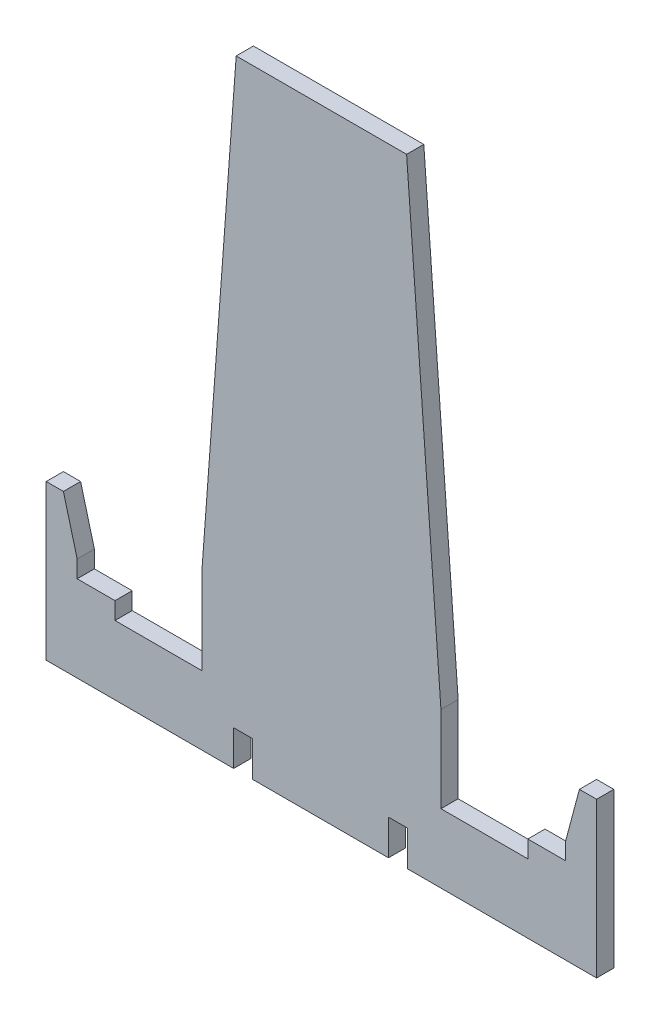
SolidWorks part; units mm, degrees
material "Plain Carbon Steel"
ref_plane "Front Plane" through (0, 0, 0) normal (0, 0, 1) x (1, 0, 0)
ref_plane "Top Plane" through (0, 0, 0) normal (0, 1, 0) x (1, 0, 0)
ref_plane "Right Plane" through (0, 0, 0) normal (1, 0, 0) x (0, 0, -1)
sketch "Model" plane through (0, 0, 0) normal (0, 0, 1) x (1, 0, 0)
  line L0 (-681.253, -108.7291) -> (-686.253, -108.7291)
  line L1 (-535.253, -123.7291) -> (-531.253, -108.7291)
  line L2 (-686.253, -153.7291) -> (-631.753, -153.7291)
  line L3 (-526.253, -153.7291) -> (-581.253, -153.7291)
  line L4 (-571.503, -133.7291) -> (-546.253, -133.7291)
  line L5 (-581.253, -153.7291) -> (-581.253, -143.4791)
  line L6 (-677.253, -128.7291) -> (-677.253, -123.7291)
  line L7 (-535.253, -128.7291) -> (-535.253, -123.7291)
  line L8 (-641.003, -133.7291) -> (-666.253, -133.7291)
  line L9 (-677.253, -123.7291) -> (-681.253, -108.7291)
  line L10 (-626.253, -153.7291) -> (-586.753, -153.7291)
  line L11 (-571.503, -108.7383) -> (-571.503, -133.7291)
  line L12 (-531.253, -108.7291) -> (-526.253, -108.7291)
  line L13 (-526.253, -108.7291) -> (-526.253, -153.7291)
  line L14 (-546.253, -128.7291) -> (-535.253, -128.7291)
  line L15 (-666.253, -128.7291) -> (-677.253, -128.7291)
  line L16 (-631.753, -143.4791) -> (-631.753, -153.7291)
  line L17 (-641.003, -108.7383) -> (-631.0208, 26.0209)
  line L18 (-626.253, -143.4791) -> (-631.753, -143.4791)
  line L19 (-586.753, -143.4791) -> (-586.753, -153.7291)
  line L20 (-641.003, -133.7291) -> (-641.003, -108.7383)
  line L21 (-666.253, -133.7291) -> (-666.253, -128.7291)
  line L22 (-686.253, -108.7291) -> (-686.253, -153.7291)
  line L23 (-626.253, -153.7291) -> (-626.253, -143.4791)
  line L24 (-581.253, -143.4791) -> (-586.753, -143.4791)
  line L25 (-546.253, -133.7291) -> (-546.253, -128.7291)
  line L26 (-581.4851, 26.0209) -> (-571.503, -108.7383)
  line L27 (-631.0208, 26.0209) -> (-581.4851, 26.0209)
  line L28 (-606.4929, -146.4501) -> (-606.059, -146.486)
  line L29 (-607.5372, -146.7467) -> (-607.2984, -146.5937)
  line L30 (-605.6937, -146.5937) -> (-605.4502, -146.7498)
  line L31 (-606.9316, -146.486) -> (-607.2984, -146.5937)
  line L32 (-607.5969, -146.8349) -> (-607.6168, -146.9309)
  line L33 (-607.6168, -146.9309) -> (-607.6168, -150.2773)
  line L34 (-607.6168, -150.2773) -> (-607.5969, -150.376)
  line L35 (-608.3802, -146.8372) -> (-608.3599, -146.9309)
  line L36 (-608.3802, -146.8372) -> (-608.4411, -146.7498)
  line L37 (-607.5372, -146.7467) -> (-607.5969, -146.8349)
  line L38 (-608.6846, -146.5937) -> (-609.0498, -146.486)
  line L39 (-605.4502, -146.7498) -> (-605.3893, -146.8372)
  line L40 (-605.3893, -146.8372) -> (-605.369, -146.9309)
  line L41 (-605.369, -146.9309) -> (-605.369, -147.2368)
  line L42 (-605.6937, -146.5937) -> (-606.059, -146.486)
  line L43 (-608.3599, -146.9309) -> (-608.3599, -147.2368)
  line L44 (-608.4411, -146.7498) -> (-608.6846, -146.5937)
  line L45 (-606.9316, -146.486) -> (-606.4929, -146.4501)
  line L46 (-607.5969, -150.376) -> (-607.5372, -150.4662)
  line L47 (-607.5372, -150.4662) -> (-607.2984, -150.6207)
  line L48 (-607.2984, -150.6207) -> (-606.9378, -150.7237)
  line L49 (-606.9378, -150.7237) -> (-606.4929, -150.7581)
  line L50 (-606.4929, -150.7581) -> (-606.0496, -150.7237)
  line L51 (-606.0496, -150.7237) -> (-605.6937, -150.6207)
  line L52 (-605.6937, -150.6207) -> (-605.4502, -150.463)
  line L53 (-610.5878, -150.376) -> (-610.6077, -150.2773)
  line L54 (-610.6077, -150.2773) -> (-610.6077, -146.9309)
  line L55 (-610.6077, -146.9309) -> (-610.5878, -146.8349)
  line L56 (-610.5281, -146.7467) -> (-610.2892, -146.5937)
  line L57 (-610.2892, -146.5937) -> (-609.9224, -146.486)
  line L58 (-609.9224, -146.486) -> (-609.4838, -146.4501)
  line L59 (-608.3802, -150.3737) -> (-608.4411, -150.463)
  line L60 (-609.0405, -150.7237) -> (-609.4838, -150.7581)
  line L61 (-610.5878, -146.8349) -> (-610.5281, -146.7467)
  line L62 (-609.4838, -146.4501) -> (-609.0498, -146.486)
  line L63 (-608.3599, -149.9714) -> (-608.3599, -150.2773)
  line L64 (-608.3599, -150.2773) -> (-608.3802, -150.3737)
  line L65 (-609.4838, -150.7581) -> (-609.9287, -150.7237)
  line L66 (-609.9287, -150.7237) -> (-610.2892, -150.6207)
  line L67 (-610.2892, -150.6207) -> (-610.5281, -150.4662)
  line L68 (-608.4411, -150.463) -> (-608.6846, -150.6207)
  line L69 (-608.6846, -150.6207) -> (-609.0405, -150.7237)
  line L70 (-610.5281, -150.4662) -> (-610.5878, -150.376)
  line L71 (-602.6997, -150.6176) -> (-603.0611, -150.7229)
  line L72 (-605.4502, -150.463) -> (-605.3893, -150.3737)
  line L73 (-605.369, -150.2773) -> (-605.369, -149.9714)
  line L74 (-603.0611, -148.121) -> (-603.5021, -148.0858)
  line L75 (-604.6059, -150.3735) -> (-604.626, -150.2773)
  line L76 (-604.1764, -148.1858) -> (-604.4075, -148.3122)
  line L77 (-603.9431, -150.7229) -> (-604.3044, -150.6176)
  line L78 (-602.4586, -150.4623) -> (-602.6997, -150.6176)
  line L79 (-603.5021, -148.0858) -> (-604.1764, -148.1858)
  line L80 (-604.626, -146.4501) -> (-604.626, -148.5666)
  line L81 (-603.0611, -150.7229) -> (-603.5021, -150.7581)
  line L82 (-602.4531, -146.4501) -> (-604.626, -146.4501)
  line L83 (-604.3044, -150.6176) -> (-604.5456, -150.4623)
  line L84 (-602.3983, -150.3735) -> (-602.4586, -150.4623)
  line L85 (-602.3983, -150.3735) -> (-602.3782, -150.2773)
  line L86 (-602.4586, -148.3816) -> (-602.3983, -148.4704)
  line L87 (-602.4586, -148.3816) -> (-602.6997, -148.2263)
  line L88 (-604.626, -148.5666) -> (-604.4075, -148.3122)
  line L89 (-603.0611, -148.121) -> (-602.6997, -148.2263)
  line L90 (-602.3782, -148.5666) -> (-602.3782, -150.2773)
  line L91 (-602.3983, -148.4704) -> (-602.3782, -148.5666)
  line L92 (-603.5021, -150.7581) -> (-603.9431, -150.7229)
  line L93 (-605.3893, -150.3737) -> (-605.369, -150.2773)
  line L94 (-604.6059, -150.3735) -> (-604.5456, -150.4623)
  line L95 (-613.1077, -148.6041) -> (-618.1077, -148.6041)
  line L96 (-616.1077, -147.6041) -> (-618.1077, -148.6041)
  line L97 (-616.1077, -149.6041) -> (-618.1077, -148.6041)
  line L98 (-599.8983, -148.6041) -> (-594.8983, -148.6041)
  line L99 (-596.8983, -149.6041) -> (-594.8983, -148.6041)
  line L100 (-596.8983, -147.6041) -> (-594.8983, -148.6041)
  line L101 (-671.753, -135.7291) -> (-671.753, -130.7291)
  line L102 (-670.753, -132.7291) -> (-671.753, -130.7291)
  line L103 (-672.753, -132.7291) -> (-671.753, -130.7291)
  line L104 (-673.623, -140.5563) -> (-673.623, -140.2503)
  line L105 (-673.6433, -140.6526) -> (-673.623, -140.5563)
  line L106 (-668.7591, -141.037) -> (-669.2001, -141.0019)
  line L107 (-675.8509, -137.1138) -> (-675.8708, -137.2098)
  line L108 (-669.8629, -140.6524) -> (-669.8026, -140.7412)
  line L109 (-671.8185, -136.723) -> (-672.4304, -139.2143)
  line L110 (-673.7041, -140.742) -> (-673.6433, -140.6526)
  line L111 (-673.9477, -140.8997) -> (-673.7041, -140.742)
  line L112 (-675.1855, -136.765) -> (-675.5523, -136.8727)
  line L113 (-669.883, -136.7291) -> (-669.883, -138.8456)
  line L114 (-669.883, -138.8456) -> (-669.6645, -138.5912)
  line L115 (-669.8629, -140.6524) -> (-669.883, -140.5563)
  line L116 (-672.4304, -139.2143) -> (-671.1691, -139.22)
  line L117 (-675.1918, -141.0027) -> (-674.7469, -141.037)
  line L118 (-669.883, -136.7291) -> (-667.7101, -136.7291)
  line L119 (-669.6645, -138.5912) -> (-669.4334, -138.4647)
  line L120 (-669.4334, -138.4647) -> (-668.7591, -138.3648)
  line L121 (-673.623, -137.2098) -> (-673.6433, -137.1162)
  line L122 (-675.8708, -137.2098) -> (-675.8708, -140.5563)
  line L123 (-675.7912, -140.7451) -> (-675.5523, -140.8997)
  line L124 (-674.7469, -141.037) -> (-674.3036, -141.0027)
  line L125 (-670.6946, -141.037) -> (-671.1691, -139.22)
  line L126 (-671.1691, -139.22) -> (-671.8185, -136.723)
  line L127 (-669.2001, -141.0019) -> (-669.5614, -140.8965)
  line L128 (-675.5523, -140.8997) -> (-675.1918, -141.0027)
  line L129 (-675.7912, -137.0257) -> (-675.8509, -137.1138)
  line L130 (-673.9477, -136.8727) -> (-674.3129, -136.765)
  line L131 (-674.3129, -136.765) -> (-674.7469, -136.7291)
  line L132 (-675.5523, -136.8727) -> (-675.7912, -137.0257)
  line L133 (-675.8509, -140.655) -> (-675.7912, -140.7451)
  line L134 (-669.8026, -140.7412) -> (-669.5614, -140.8965)
  line L135 (-673.623, -137.2098) -> (-673.623, -137.5158)
  line L136 (-674.7469, -136.7291) -> (-675.1855, -136.765)
  line L137 (-675.8708, -140.5563) -> (-675.8509, -140.655)
  line L138 (-673.6433, -137.1162) -> (-673.7041, -137.0288)
  line L139 (-674.3036, -141.0027) -> (-673.9477, -140.8997)
  line L140 (-673.7041, -137.0288) -> (-673.9477, -136.8727)
  line L141 (-667.6553, -140.6524) -> (-667.7156, -140.7412)
  line L142 (-667.7156, -140.7412) -> (-667.9567, -140.8965)
  line L143 (-667.9567, -138.5053) -> (-667.7156, -138.6606)
  line L144 (-667.9567, -140.8965) -> (-668.3181, -141.0019)
  line L145 (-668.3181, -138.3999) -> (-667.9567, -138.5053)
  line L146 (-668.7591, -138.3648) -> (-668.3181, -138.3999)
  line L147 (-672.4304, -139.2143) -> (-672.8799, -141.037)
  line L148 (-667.7156, -138.6606) -> (-667.6553, -138.7494)
  line L149 (-667.6352, -140.5563) -> (-667.6553, -140.6524)
  line L150 (-668.3181, -141.0019) -> (-668.7591, -141.037)
  line L151 (-667.6553, -138.7494) -> (-667.6352, -138.8456)
  line L152 (-667.6352, -138.8456) -> (-667.6352, -140.5563)
  line L153 (-613.8517, -72.7044) -> (-613.1305, -72.9104)
  line L154 (-610.6424, -72.7044) -> (-610.1553, -72.3891)
  line L155 (-610.1553, -72.3891) -> (-610.0336, -72.2103)
  line L156 (-613.8517, -72.7044) -> (-614.3294, -72.3953)
  line L157 (-614.4488, -72.215) -> (-614.4886, -72.0176)
  line L158 (-609.993, -65.9366) -> (-609.993, -65.3247)
  line L159 (-610.6424, -64.6504) -> (-611.3729, -64.435)
  line L160 (-613.1305, -72.9104) -> (-612.2408, -72.9791)
  line L161 (-614.4488, -65.1328) -> (-614.3294, -64.9564)
  line L162 (-610.6424, -72.7044) -> (-611.3541, -72.9104)
  line L163 (-614.3294, -64.9564) -> (-613.8517, -64.6504)
  line L164 (-612.2408, -64.3632) -> (-613.1181, -64.435)
  line L165 (-614.3294, -72.3953) -> (-614.4488, -72.215)
  line L166 (-609.993, -72.0176) -> (-610.0336, -72.2103)
  line L167 (-614.4886, -72.0176) -> (-614.4886, -65.3247)
  line L168 (-614.4886, -65.3247) -> (-614.4488, -65.1328)
  line L169 (-609.993, -71.4057) -> (-609.993, -72.0176)
  line L170 (-610.1553, -64.9626) -> (-610.0336, -65.1374)
  line L171 (-611.3541, -72.9104) -> (-612.2408, -72.9791)
  line L172 (-609.993, -65.3247) -> (-610.0336, -65.1374)
  line L173 (-610.1553, -64.9626) -> (-610.6424, -64.6504)
  line L174 (-611.3729, -64.435) -> (-612.2408, -64.3632)
  line L175 (-613.1181, -64.435) -> (-613.8517, -64.6504)
  line L176 (-606.4713, -64.3632) -> (-605.6128, -64.435)
  line L177 (-604.2649, -72.215) -> (-604.2235, -72.0175)
  line L178 (-604.2235, -65.3248) -> (-604.2649, -65.1375)
  line L179 (-608.5069, -64.3632) -> (-608.5069, -68.5834)
  line L180 (-604.2235, -69.5075) -> (-604.3391, -69.2015)
  line L181 (-600.2652, -72.9791) -> (-601.1471, -72.9088)
  line L182 (-602.513, -72.0176) -> (-602.4728, -72.21)
  line L183 (-605.3568, -68.7208) -> (-606.4713, -68.5834)
  line L184 (-605.6128, -64.435) -> (-604.8854, -64.6504)
  line L185 (-598.1672, -64.3632) -> (-602.513, -64.3632)
  line L186 (-604.8854, -72.7043) -> (-605.6066, -72.9104)
  line L187 (-604.6856, -68.9331) -> (-605.3568, -68.7208)
  line L188 (-604.389, -64.9626) -> (-604.2649, -65.1375)
  line L189 (-604.3391, -67.9688) -> (-604.6856, -68.2466)
  line L190 (-601.1471, -72.9088) -> (-601.8699, -72.6981)
  line L191 (-608.5069, -64.3632) -> (-606.4713, -64.3632)
  line L192 (-606.4713, -72.9791) -> (-605.6066, -72.9104)
  line L193 (-604.2235, -72.0175) -> (-604.2235, -69.5075)
  line L194 (-604.3391, -69.2015) -> (-604.6856, -68.9331)
  line L195 (-602.3522, -72.3875) -> (-602.4728, -72.21)
  line L196 (-604.2235, -67.66) -> (-604.2235, -65.3248)
  line L197 (-606.4713, -68.5834) -> (-608.5069, -68.5834)
  line L198 (-608.5069, -72.9791) -> (-606.4713, -72.9791)
  line L199 (-605.3693, -68.4558) -> (-606.4713, -68.5834)
  line L200 (-605.3693, -68.4558) -> (-604.6856, -68.2466)
  line L201 (-604.389, -64.9626) -> (-604.8854, -64.6504)
  line L202 (-604.2235, -67.66) -> (-604.3391, -67.9688)
  line L203 (-601.8699, -72.6981) -> (-602.3522, -72.3875)
  line L204 (-604.8854, -72.7043) -> (-604.389, -72.3953)
  line L205 (-604.2649, -72.215) -> (-604.389, -72.3953)
  line L206 (-598.0174, -68.5963) -> (-598.0174, -72.0176)
  line L207 (-598.1781, -72.3875) -> (-598.6605, -72.6981)
  line L208 (-600.2652, -67.6347) -> (-599.3832, -67.7049)
  line L209 (-602.513, -68.5963) -> (-602.0759, -68.0874)
  line L210 (-598.6605, -72.6981) -> (-599.3832, -72.9088)
  line L211 (-601.6139, -67.8345) -> (-600.2652, -67.6347)
  line L212 (-598.6605, -67.9156) -> (-598.1781, -68.2263)
  line L213 (-599.3832, -72.9088) -> (-600.2652, -72.9791)
  line L214 (-598.1781, -68.2263) -> (-598.0576, -68.4039)
  line L215 (-602.513, -64.3632) -> (-602.513, -68.5963)
  line L216 (-608.5069, -68.5834) -> (-608.5069, -72.9791)
  line L217 (-598.0576, -68.4039) -> (-598.0174, -68.5963)
  line L218 (-598.0174, -72.0176) -> (-598.0576, -72.21)
  line L219 (-599.3832, -67.7049) -> (-598.6605, -67.9156)
  line L220 (-598.0576, -72.21) -> (-598.1781, -72.3875)
  line L221 (-602.0759, -68.0874) -> (-601.6139, -67.8345)
  line L222 (-614.4886, -73.9791) -> (-598.0174, -73.9791)
  line L223 (-540.753, -135.7291) -> (-540.753, -130.7291)
  line L224 (-539.753, -132.7291) -> (-540.753, -130.7291)
  line L225 (-541.753, -132.7291) -> (-540.753, -130.7291)
  line L226 (-542.623, -140.5563) -> (-542.623, -140.2503)
  line L227 (-542.6433, -140.6526) -> (-542.623, -140.5563)
  line L228 (-537.7591, -141.037) -> (-538.2001, -141.0019)
  line L229 (-544.8509, -137.1138) -> (-544.8708, -137.2098)
  line L230 (-538.8629, -140.6524) -> (-538.8026, -140.7412)
  line L231 (-540.8185, -136.723) -> (-541.4304, -139.2143)
  line L232 (-542.7041, -140.742) -> (-542.6433, -140.6526)
  line L233 (-542.9477, -140.8997) -> (-542.7041, -140.742)
  line L234 (-544.1855, -136.765) -> (-544.5523, -136.8727)
  line L235 (-538.883, -136.7291) -> (-538.883, -138.8456)
  line L236 (-538.883, -138.8456) -> (-538.6645, -138.5912)
  line L237 (-538.8629, -140.6524) -> (-538.883, -140.5563)
  line L238 (-541.4304, -139.2143) -> (-540.1691, -139.22)
  line L239 (-544.1918, -141.0027) -> (-543.7469, -141.037)
  line L240 (-538.883, -136.7291) -> (-536.7101, -136.7291)
  line L241 (-538.6645, -138.5912) -> (-538.4334, -138.4647)
  line L242 (-538.4334, -138.4647) -> (-537.7591, -138.3648)
  line L243 (-542.623, -137.2098) -> (-542.6433, -137.1162)
  line L244 (-544.8708, -137.2098) -> (-544.8708, -140.5563)
  line L245 (-544.7912, -140.7451) -> (-544.5523, -140.8997)
  line L246 (-543.7469, -141.037) -> (-543.3036, -141.0027)
  line L247 (-539.6946, -141.037) -> (-540.1691, -139.22)
  line L248 (-540.1691, -139.22) -> (-540.8185, -136.723)
  line L249 (-538.2001, -141.0019) -> (-538.5614, -140.8965)
  line L250 (-544.5523, -140.8997) -> (-544.1918, -141.0027)
  line L251 (-544.7912, -137.0257) -> (-544.8509, -137.1138)
  line L252 (-542.9477, -136.8727) -> (-543.3129, -136.765)
  line L253 (-543.3129, -136.765) -> (-543.7469, -136.7291)
  line L254 (-544.5523, -136.8727) -> (-544.7912, -137.0257)
  line L255 (-544.8509, -140.655) -> (-544.7912, -140.7451)
  line L256 (-538.8026, -140.7412) -> (-538.5614, -140.8965)
  line L257 (-542.623, -137.2098) -> (-542.623, -137.5158)
  line L258 (-543.7469, -136.7291) -> (-544.1855, -136.765)
  line L259 (-544.8708, -140.5563) -> (-544.8509, -140.655)
  line L260 (-542.6433, -137.1162) -> (-542.7041, -137.0288)
  line L261 (-543.3036, -141.0027) -> (-542.9477, -140.8997)
  line L262 (-542.7041, -137.0288) -> (-542.9477, -136.8727)
  line L263 (-536.6553, -140.6524) -> (-536.7156, -140.7412)
  line L264 (-536.7156, -140.7412) -> (-536.9567, -140.8965)
  line L265 (-536.9567, -138.5053) -> (-536.7156, -138.6606)
  line L266 (-536.9567, -140.8965) -> (-537.3181, -141.0019)
  line L267 (-537.3181, -138.3999) -> (-536.9567, -138.5053)
  line L268 (-537.7591, -138.3648) -> (-537.3181, -138.3999)
  line L269 (-541.4304, -139.2143) -> (-541.8799, -141.037)
  line L270 (-536.7156, -138.6606) -> (-536.6553, -138.7494)
  line L271 (-536.6352, -140.5563) -> (-536.6553, -140.6524)
  line L272 (-537.3181, -141.0019) -> (-537.7591, -141.037)
  line L273 (-536.6553, -138.7494) -> (-536.6352, -138.8456)
  line L274 (-536.6352, -138.8456) -> (-536.6352, -140.5563)
sketch "Sketch2" plane through (0, 0, 0) normal (0, 0, 1) x (1, 0, 0)
  line L0 (-641.003, -108.7383) -> (-631.0208, 26.0209) construction
  line L1 (-641.003, -133.7291) -> (-641.003, -108.7383) construction
  line L2 (-641.003, -133.7291) -> (-666.253, -133.7291) construction
  line L3 (-666.253, -133.7291) -> (-666.253, -128.7291) construction
  line L4 (-666.253, -128.7291) -> (-677.253, -128.7291) construction
  line L5 (-677.253, -128.7291) -> (-677.253, -123.7291) construction
  line L6 (-677.253, -123.7291) -> (-681.253, -108.7291) construction
  line L7 (-681.253, -108.7291) -> (-686.253, -108.7291) construction
  line L8 (-686.253, -108.7291) -> (-686.253, -153.7291) construction
  line L9 (-686.253, -153.7291) -> (-631.753, -153.7291) construction
  line L10 (-631.753, -143.4791) -> (-631.753, -153.7291) construction
  line L11 (-626.253, -143.4791) -> (-631.753, -143.4791) construction
  line L12 (-626.253, -153.7291) -> (-626.253, -143.4791) construction
  line L13 (-626.253, -153.7291) -> (-586.753, -153.7291) construction
  line L14 (-586.753, -143.4791) -> (-586.753, -153.7291) construction
  line L15 (-581.253, -143.4791) -> (-586.753, -143.4791) construction
  line L16 (-581.253, -153.7291) -> (-581.253, -143.4791) construction
  line L17 (-526.253, -153.7291) -> (-581.253, -153.7291) construction
  line L18 (-526.253, -108.7291) -> (-526.253, -153.7291) construction
  line L19 (-531.253, -108.7291) -> (-526.253, -108.7291) construction
  line L20 (-535.253, -123.7291) -> (-531.253, -108.7291) construction
  line L21 (-535.253, -128.7291) -> (-535.253, -123.7291) construction
  line L22 (-546.253, -128.7291) -> (-535.253, -128.7291) construction
  line L23 (-546.253, -133.7291) -> (-546.253, -128.7291) construction
  line L24 (-571.503, -133.7291) -> (-546.253, -133.7291) construction
  line L25 (-571.503, -108.7383) -> (-571.503, -133.7291) construction
  line L26 (-581.4851, 26.0209) -> (-571.503, -108.7383) construction
  line L27 (-631.0208, 26.0209) -> (-581.4851, 26.0209) construction
  line L28 (-641.003, -108.7383) -> (-631.0208, 26.0209)
  line L29 (-641.003, -133.7291) -> (-641.003, -108.7383)
  line L30 (-641.003, -133.7291) -> (-666.253, -133.7291)
  line L31 (-666.253, -133.7291) -> (-666.253, -128.7291)
  line L32 (-666.253, -128.7291) -> (-677.253, -128.7291)
  line L33 (-677.253, -128.7291) -> (-677.253, -123.7291)
  line L34 (-677.253, -123.7291) -> (-681.253, -108.7291)
  line L35 (-681.253, -108.7291) -> (-686.253, -108.7291)
  line L36 (-686.253, -108.7291) -> (-686.253, -153.7291)
  line L37 (-686.253, -153.7291) -> (-631.753, -153.7291)
  line L38 (-631.753, -143.4791) -> (-631.753, -153.7291)
  line L39 (-626.253, -143.4791) -> (-631.753, -143.4791)
  line L40 (-626.253, -153.7291) -> (-626.253, -143.4791)
  line L41 (-626.253, -153.7291) -> (-586.753, -153.7291)
  line L42 (-586.753, -143.4791) -> (-586.753, -153.7291)
  line L43 (-581.253, -143.4791) -> (-586.753, -143.4791)
  line L44 (-581.253, -153.7291) -> (-581.253, -143.4791)
  line L45 (-526.253, -153.7291) -> (-581.253, -153.7291)
  line L46 (-526.253, -108.7291) -> (-526.253, -153.7291)
  line L47 (-531.253, -108.7291) -> (-526.253, -108.7291)
  line L48 (-535.253, -123.7291) -> (-531.253, -108.7291)
  line L49 (-535.253, -128.7291) -> (-535.253, -123.7291)
  line L50 (-546.253, -128.7291) -> (-535.253, -128.7291)
  line L51 (-546.253, -133.7291) -> (-546.253, -128.7291)
  line L52 (-571.503, -133.7291) -> (-546.253, -133.7291)
  line L53 (-571.503, -108.7383) -> (-571.503, -133.7291)
  line L54 (-581.4851, 26.0209) -> (-571.503, -108.7383)
  line L55 (-631.0208, 26.0209) -> (-581.4851, 26.0209)
  line L56 (-606.503, -153.7291) -> (-606.503, -36.24) construction
extrude "Boss-Extrude1" add sketch "Sketch2" along normal mid plane 5
ref_plane "Plane1" through (-606.503, 0, 0) normal (1, 0, 0) x (0, 0, -1)
